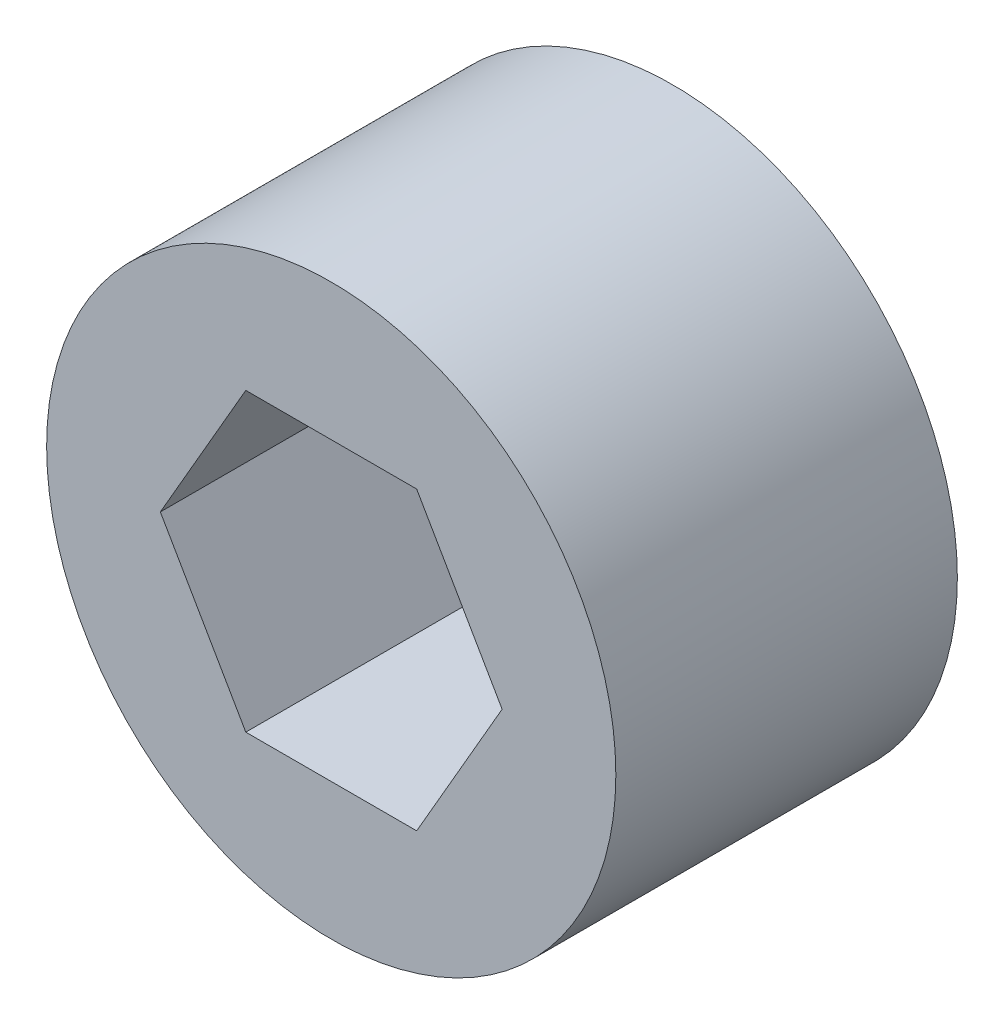
SolidWorks part; units mm, degrees
ref_plane "Front Plane" through (0, 0, 0) normal (0, 0, 1) x (1, 0, 0)
ref_plane "Top Plane" through (0, 0, 0) normal (0, 1, 0) x (1, 0, 0)
ref_plane "Right Plane" through (0, 0, 0) normal (1, 0, 0) x (0, 0, -1)
sketch "Sketch1" plane through (0, 0, 0) normal (0, 0, 1) x (1, 0, 0)
  line L1 (3.8128, -6.604) -> (7.6256, 0)
  line L2 (7.6256, 0) -> (3.8128, 6.604)
  line L3 (3.8128, 6.604) -> (-3.8128, 6.604)
  line L4 (-3.8128, 6.604) -> (-7.6256, 0)
  line L5 (-7.6256, 0) -> (-3.8128, -6.604)
  line L6 (-3.8128, -6.604) -> (3.8128, -6.604)
  circle A0 centre (0, 0) radius 6.604 construction
  circle A1 centre (0, 0) radius 12.7
  dimension "D2" = 25.4
  dimension "D1" = 13.208
extrude "Boss-Extrude1" add sketch "Sketch1" along normal blind 15.24
